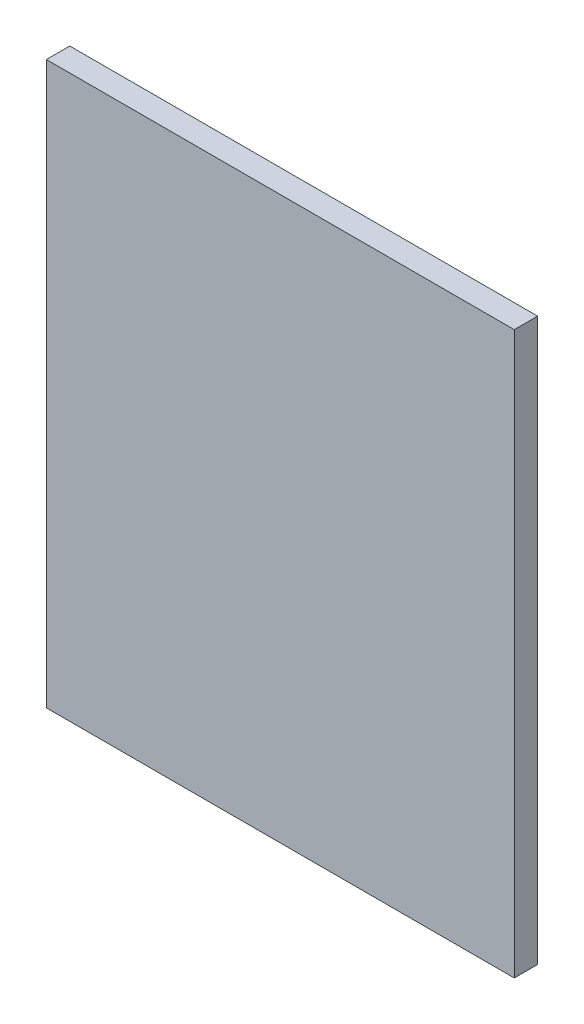
SolidWorks part; units mm, degrees
ref_plane "Front Plane" through (0, 0, 0) normal (0, 0, 1) x (1, 0, 0)
ref_plane "Top Plane" through (0, 0, 0) normal (0, 1, 0) x (1, 0, 0)
ref_plane "Right Plane" through (0, 0, 0) normal (1, 0, 0) x (0, 0, -1)
sketch "Sketch1" plane through (0, 0, 0) normal (0, 0, 1) x (1, 0, 0)
  line L0 (-764.3836, 445.8904) -> (-764.3836, -754.1096)
  line L1 (-764.3836, -754.1096) -> (235.6164, -754.1096)
  line L2 (235.6164, -754.1096) -> (235.6164, 445.8904)
  line L3 (235.6164, 445.8904) -> (-764.3836, 445.8904)
  dimension "D1" = 1200
  dimension "D2" = 1000
extrude "Boss-Extrude1" add sketch "Sketch1" along normal blind 50 contours L3 L0 L1 L2
